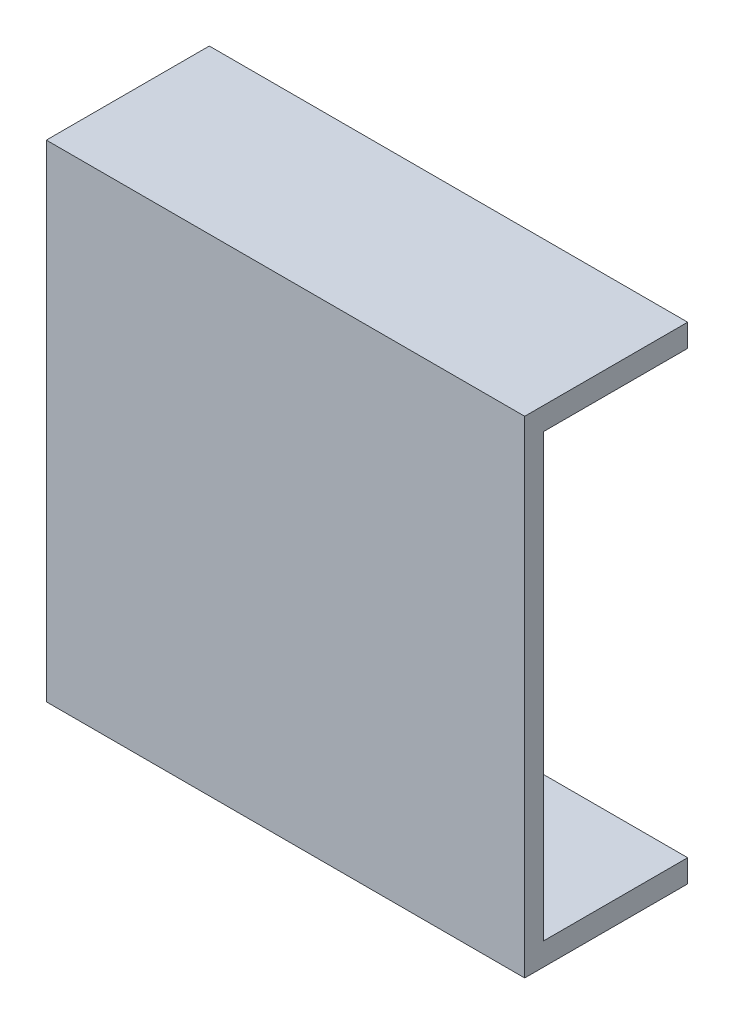
SolidWorks part; units mm, degrees
ref_plane "前视" through (0, 0, 0) normal (0, 0, 1) x (1, 0, 0)
ref_plane "上视" through (0, 0, 0) normal (0, 1, 0) x (1, 0, 0)
ref_plane "右视" through (0, 0, 0) normal (1, 0, 0) x (0, 0, -1)
sketch "草图1" plane through (0, 0, 0) normal (0, 0, 1) x (1, 0, 0)
  line L0 (0, 0) -> (0, 94.429) construction
  line L1 (-147.5, 300) -> (147.5, 300)
  line L2 (-147.5, 300) -> (-147.5, 0)
  line L3 (-147.5, 0) -> (147.5, 0)
  line L4 (147.5, 300) -> (147.5, 0)
  line L5 (-203.17, 70) -> (213.5889, 70) construction
  line L6 (-203.17, 150) -> (228.17, 150) construction
  line L7 (-203.17, 230) -> (213.5889, 230) construction
  line L8 (92.5, -78.7935) -> (92.5, 321.0346) construction
  line L9 (12.5, -78.7935) -> (12.5, 279.3587) construction
  line L10 (-67.5, -78.7935) -> (-67.5, 279.3587) construction
  line L11 (-244.8459, 0) -> (338.6166, 0) construction
  dimension "D1" = 300
  dimension "D2" = 295
  dimension "D3" = 70
  dimension "D4" = 80
  dimension "D5" = 80
  dimension "D6" = 55
  dimension "D7" = 80
  dimension "D8" = 80
extrude "基体-拉伸" add sketch "草图1" along normal blind 11.5
sketch "草图2" plane through (0, 0, 0) normal (0, 0, -1) x (-1, 0, 0)
  line L0 (147.5, 300) -> (147.5, 0) construction
  line L1 (-147.5, 300) -> (147.5, 300)
  line L2 (-147.5, 300) -> (-147.5, 286)
  line L3 (-147.5, 286) -> (147.5, 286)
  line L4 (147.5, 300) -> (147.5, 286)
  line L6 (-147.5, 0) -> (147.5, 0)
  line L7 (-147.5, 0) -> (-147.5, 14)
  line L8 (-147.5, 14) -> (147.5, 14)
  line L9 (147.5, 0) -> (147.5, 14)
  dimension "D1" = 14
  dimension "D2" = 14
extrude "凸台-拉伸1" add sketch "草图2" along normal blind 89
